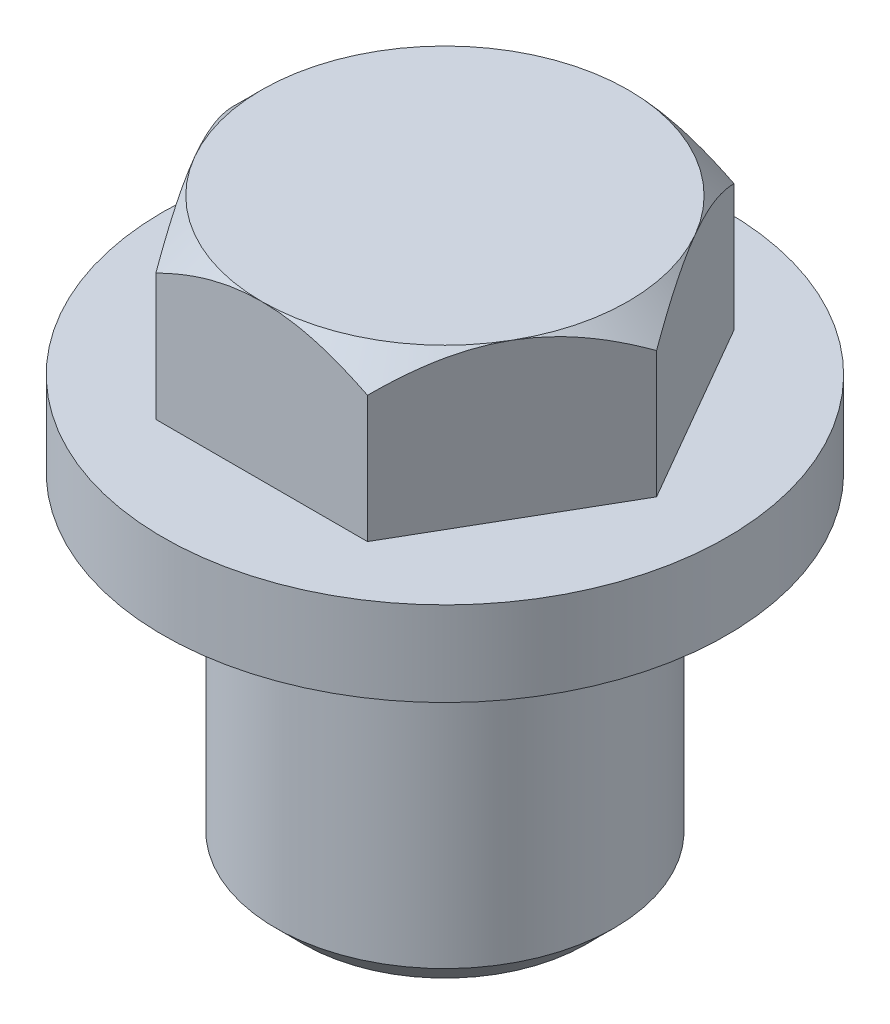
SolidWorks part; units mm, degrees
ref_plane "Front Plane" through (0, 0, 0) normal (0, 0, 1) x (1, 0, 0)
ref_plane "Top Plane" through (0, 0, 0) normal (0, 1, 0) x (1, 0, 0)
ref_plane "Right Plane" through (0, 0, 0) normal (1, 0, 0) x (0, 0, -1)
sketch "Sketch1" plane through (0, 0, 0) normal (0, 0, 1) x (1, 0, 0)
  line L0 (0, 0) -> (-5, 0)
  line L1 (-6, 1) -> (-6, 10)
  line L2 (-6, 12) -> (-10, 12)
  line L3 (-10, 12) -> (-10, 15)
  line L4 (-10, 15) -> (0, 15)
  line L5 (0, 15) -> (0, 0)
  line L6 (-5, 0) -> (-6, 1)
  line L7 (-6, 10) -> (0, 10) construction
  arc A0 (-6, 10) -> (-6, 12) centre (-6, 11) ccw
  point P1 (-6, 0)
  dimension "D3" = 2
  dimension "D1" = 6
  dimension "D2" = 12
  dimension "D4" = 3
  dimension "D5" = 10
revolve "Revolve1" add sketch "Sketch1" angle 360 about L5
sketch "Sketch2" plane through (0, 15, 0) normal (0, 1, 0) x (1, 0, 0)
  line L1 (-3.7528, 6.5) -> (-7.5056, 0)
  line L2 (-7.5056, 0) -> (-3.7528, -6.5)
  line L3 (-3.7528, -6.5) -> (3.7528, -6.5)
  line L4 (3.7528, -6.5) -> (7.5056, 0)
  line L5 (7.5056, 0) -> (3.7528, 6.5)
  line L6 (3.7528, 6.5) -> (-3.7528, 6.5)
  circle A0 centre (0, 0) radius 6.5 construction
  dimension "D1" = 13
extrude "Boss-Extrude1" add sketch "Sketch2" along normal blind 5.5
sketch "Sketch3" plane through (0, 20.5, 0) normal (0, 1, 0) x (1, 0, 0)
  line L0 (3.7528, 6.5) -> (-3.7528, 6.5) construction
  circle A0 centre (0, 0) radius 6.5
extrude "Cut-Extrude1" cut sketch "Sketch3" against normal blind 5.5 draft 45 flip side to cut
